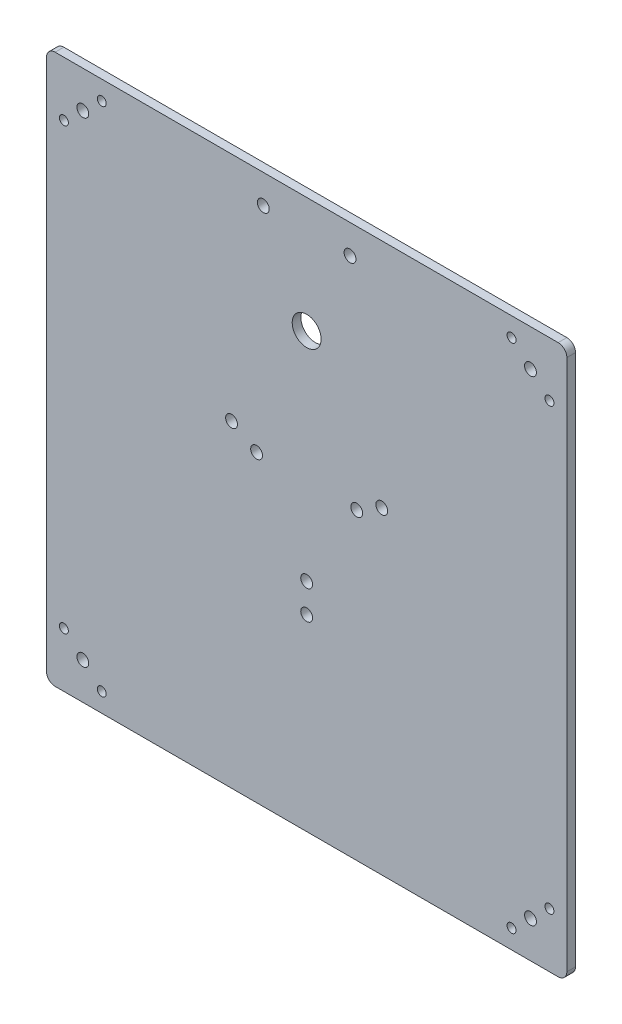
SolidWorks part; units mm, degrees
material "Thornel Mat VMA"
ref_plane "Front Plane" through (0, 0, 0) normal (0, 0, 1) x (1, 0, 0)
ref_plane "Top Plane" through (0, 0, 0) normal (0, 1, 0) x (1, 0, 0)
ref_plane "Right Plane" through (0, 0, 0) normal (1, 0, 0) x (0, 0, -1)
sketch "Sketch1" plane through (0, 0, 0) normal (0, 0, 1) x (1, 0, 0)
  line L1 (-90, -95) -> (90, -95)
  line L2 (-90, -95) -> (-90, 95)
  line L3 (-90, 95) -> (90, 95)
  line L4 (90, -95) -> (90, 95)
  line L5 (-90, -95) -> (90, 95) construction
  line L6 (-90, 95) -> (90, -95) construction
  point P0 (0, 0)
  dimension "D1" = 180
  dimension "D2" = 190
extrude "Boss-Extrude1" add sketch "Sketch1" along normal blind 3
fillet "Fillet1" radius 3 4 edges at (90, -95, 1.5) (-90, -95, 1.5) (-90, 95, 1.5) (90, 95, 1.5)
sketch "Sketch2" plane through (0, 0, 0) normal (0, 0, -1) x (-1, 0, 0)
  line L0 (-77.4295, 82.2688) -> (-72.7692, 86.6549) construction
  line L1 (-77.4295, -82.2688) -> (77.4295, -82.2688) construction
  line L2 (-77.4295, -82.2688) -> (-77.4295, 82.2688) construction
  line L3 (-77.4295, 82.2688) -> (77.4295, 82.2688) construction
  line L4 (77.4295, -82.2688) -> (77.4295, 82.2688) construction
  line L5 (-77.4295, -82.2688) -> (77.4295, 82.2688) construction
  line L6 (-77.4295, 82.2688) -> (77.4295, -82.2688) construction
  line L7 (77.4295, 82.2688) -> (74.0252, 85.4728) construction
  line L8 (-77.4295, -82.2688) -> (-81.9959, -77.971) construction
  line L9 (77.4295, -82.2688) -> (85.8934, -74.3028) construction
  circle A0 centre (-77.4295, 82.2688) radius 2.05
  circle A1 centre (77.4295, 82.2688) radius 2.05
  circle A2 centre (-77.4295, -82.2688) radius 2.05
  circle A3 centre (77.4295, -82.2688) radius 2.05
  circle A4 centre (-70.8757, 88.4371) radius 1.55
  circle A5 centre (-83.9833, 76.1006) radius 1.55
  circle A6 centre (70.8757, 88.4371) radius 1.55
  circle A7 centre (83.9833, 76.1006) radius 1.55
  circle A8 centre (-83.9833, -76.1006) radius 1.55
  circle A9 centre (-70.8757, -88.4371) radius 1.55
  circle A10 centre (83.9833, -76.1006) radius 1.55
  circle A11 centre (70.8757, -88.4371) radius 1.55
  point P0 (0, 0)
  dimension "D3" = 4.1
  dimension "D4" = 3.1
  dimension "D6" = 18
  dimension "D7" = 18
  dimension "D8" = 18
  dimension "D1" = 164.5377
  dimension "D2" = 154.859
  dimension "D5" = 18
extrude "Cut-Extrude1" cut sketch "Sketch2" against normal up to surface (3 mm away) up to face at (0, 0, 3)
sketch "草图2" plane through (0, 0, 3) normal (0, 0, 1) x (1, 0, 0)
  line L1 (0, 95) -> (0, -65) construction
  line L2 (87, 95) -> (-87, 95) construction
  line L3 (-90, 0) -> (90, 0) construction
  line L5 (90, -92) -> (90, 92) construction
  line L6 (-90, 92) -> (-90, -92) construction
  circle A0 centre (-30, 0) radius 2.05 construction
  circle A1 centre (-20, 0) radius 2.05 construction
  circle A4 centre (30, 0) radius 2.05 construction
  circle A5 centre (20, 0) radius 2.05 construction
  circle A6 centre (0, -20) radius 2.05
  circle A7 centre (0, -30) radius 2.05
  circle A8 centre (-17.3205, 10) radius 2.05
  circle A9 centre (-25.9808, 15) radius 2.05
  circle A10 centre (17.3205, 10) radius 2.05
  circle A11 centre (25.9808, 15) radius 2.05
  point P33 (0, 0)
  dimension "D1" = 4.1
  dimension "D2" = 20
  dimension "D4" = 4.1
  dimension "D3" = 10
  dimension "D5" = 10
  dimension "D6" = 20
  dimension "D7" = 3
extrude "切除-拉伸1" cut sketch "草图2" against normal up to next
sketch "草图3" plane through (0, 0, 0) normal (0, 0, -1) x (-1, 0, 0)
  line L0 (0, 75) -> (0, 50.3952) construction
  line L2 (-87, 95) -> (87, 95) construction
  circle A0 centre (-15, 85) radius 2.05
  circle A1 centre (15, 85) radius 2.05
  dimension "D1" = 4.1
  dimension "D2" = 15
  dimension "D3" = 10
extrude "切除-拉伸2" cut sketch "草图3" against normal up to next
sketch "草图4" plane through (0, 0, 3) normal (0, 0, 1) x (1, 0, 0)
  line L0 (0, 90) -> (0, 50.4777) construction
  line L2 (87, 95) -> (-87, 95) construction
  circle A0 centre (0, 55) radius 5
  dimension "D1" = 10
  dimension "D2" = 40
extrude "切除-拉伸3" cut sketch "草图4" against normal up to next
